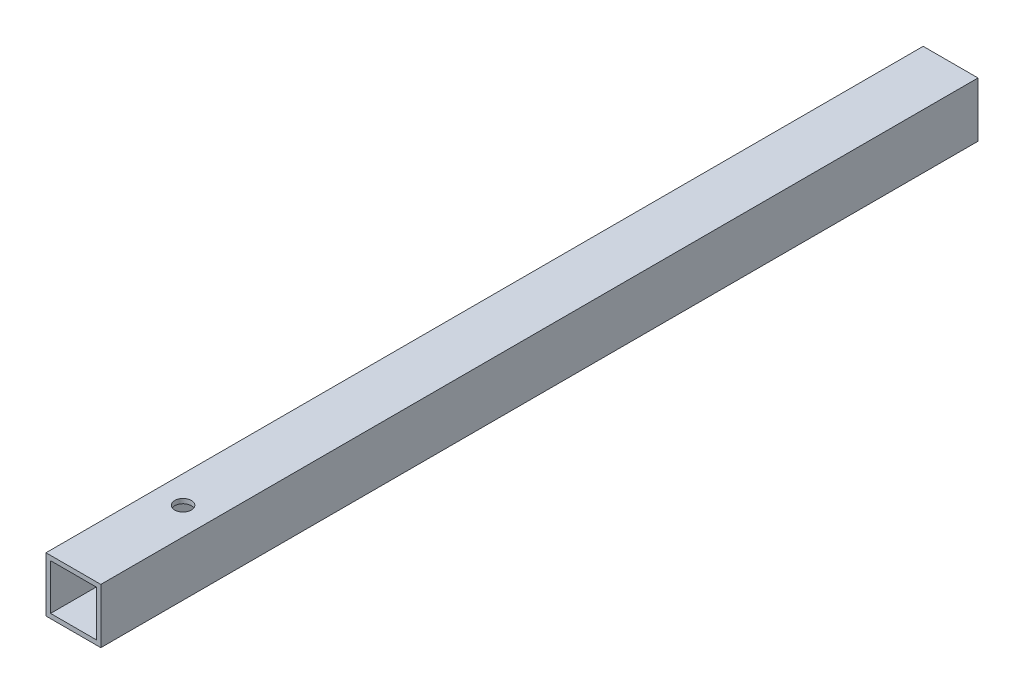
SolidWorks part; units mm, degrees
ref_plane "Front Plane" through (0, 0, 0) normal (0, 0, 1) x (1, 0, 0)
ref_plane "Top Plane" through (0, 0, 0) normal (0, 1, 0) x (1, 0, 0)
ref_plane "Right Plane" through (0, 0, 0) normal (1, 0, 0) x (0, 0, -1)
sketch "Sketch1" plane through (0, 0, 0) normal (0, 0, 1) x (0, -1, 0)
  line L1 (-9.525, 9.525) -> (9.525, 9.525)
  line L2 (-9.525, 9.525) -> (-9.525, -9.525)
  line L3 (-9.525, -9.525) -> (9.525, -9.525)
  line L4 (9.525, 9.525) -> (9.525, -9.525)
  line L5 (-9.525, 9.525) -> (9.525, -9.525) construction
  line L6 (-9.525, -9.525) -> (9.525, 9.525) construction
  line L7 (-7.9375, 7.9375) -> (7.9375, 7.9375)
  line L8 (-7.9375, 7.9375) -> (-7.9375, -7.9375)
  line L9 (-7.9375, -7.9375) -> (7.9375, -7.9375)
  line L10 (7.9375, 7.9375) -> (7.9375, -7.9375)
  line L11 (-7.9375, 7.9375) -> (7.9375, -7.9375) construction
  line L12 (-7.9375, -7.9375) -> (7.9375, 7.9375) construction
  point P0 (0, 0)
  point P5 (0, 0)
  dimension "D1" = 15.875
  dimension "D2" = 19.05
extrude "Boss-Extrude1" add sketch "Sketch1" along normal mid plane 304.8
sketch "Sketch2" plane through (0, 9.525, 0) normal (0, 1, 0) x (1, 0, 0)
  line L0 (0, -152.4) -> (0, -114.3) construction
  line L1 (9.525, -152.4) -> (-9.525, -152.4) construction
  circle A0 centre (0, -114.3) radius 2.8956
  dimension "D1" = 5.7912
  dimension "D2" = 38.1
extrude "Baseplate Mount Hole" cut sketch "Sketch2" against normal through all
sketch "Sketch3" plane through (-9.525, 0, 0) normal (-1, 0, 0) x (0, 0, 1)
  line L0 (-25.4, 0) -> (0, 0) construction
  line L1 (152.4, 9.525) -> (152.4, -9.525) construction
  circle A0 centre (-25.4, 0) radius 2.4257
  dimension "D2" = 4.8514
  dimension "D1" = 177.8
extrude "PS Bracket Mount Hole" cut sketch "Sketch3" against normal up to next
equation "\"Height\"= 32in"
equation "\"Width\"= 23in"
equation "\"Depth\"= 20in"
equation "\"Plexi\"= .121in"
equation "\"MagnetThickness\"=3mm"
equation "\"MagnetDiameter\"=12mm"
equation "\"DoorPlexi\" = \"Plexi\""
equation "\"BasePlateThickness\" = 0.5in"
equation "\"BasePlateWidth\" = \"Width\"+\"EBWidth\"-2*\"Plexi\""
equation "\"BasePlateDepth\" = \"Depth\"-\"Plexi\"-\"DoorPlexi\""
equation "\"Boxsize\" = .75in"
equation "\"Boxinner\" = .625in"
equation "\"CornerCube\" = 0.75in"
equation "\"FingerLength\" = 1.125in"
equation "\"FingerWidth\" = .625in"
equation "\"Cutwidth\"= .016in"
equation "\"Earsize\"= 1in + \"Cutwidth\" /2"
equation "\"Slotsize\" = 1in - \"CutWidth\" / 2"
equation "\"InnerWidth\" = \"Width\" - 2* \"Plexi\""
equation "\"InnerHeight\" = \"Height\" -2 * \"Plexi\""
equation "\"InnerDepth\" = \"Depth\" - 2*\"Plexi\""
equation "\"RearNumHoles\" = 7"
equation "\"RearHolesBorder\" = 2.2"
equation "\"RearHoleSpacing\" = (\"Width\" - 2*\"RearHolesBorder\") / (\"RearNumHoles\"-1)"
equation "\"RearBarLength\" = (\"InnerWidth\"-2*\"CornerCube\")"
equation "\"RearTopNumHoles\" = 6"
equation "\"RearTopHolesBorder\" = 2.5"
equation "\"RearTopHolesSpacing\" = (\"Width\" - 2*\"RearTopHolesBorder\") / (\"RearTopNumHoles\"-1)"
equation "\"SideTopNumHoles\" = 5"
equation "\"SideTopHoleOffset\"=\"CornerCube\"+\"FingerLength\"+\"Plexi\"+.5"
equation "\"SideHorizNumHoles\" = 6"
equation "\"SideHorizHoleBorder\" = 2.25"
equation "\"SideVertBarLength\"=\"Height\"-\"BasePlateThickness\"-2*\"CornerCube\"-\"Plexi\""
equation "\"SideVertNumHoles\" = 6"
equation "\"SideVertHolesBorder\" = \"CornerCube\"+\"FingerLength\"+.9"
equation "\"SideVertHoleSpacing\" = (\"InnerHeight\" - 2*\"SideVertHolesBorder\") / (\"SideVertNumHoles\"-1)"
equation "\"RearSideVertNumHoles\" = 7"
equation "\"RearSideVertHolesBorder\" = 2.5"
equation "\"RearSideVertHoleSpacing\" = (\"InnerHeight\" - 2*\"RearSideVertHolesBorder\") / (\"RearSideVertNumHoles\"-1)"
equation "\"RivetDia\" = .228in"
equation "\"SlotDepth\" = \"Plexi\" + 0.75in + .005in"
equation "\"SideSlotWidth\"   = \"Plexi\"+.005in"
equation "\"SidePanelVertSpacing\" = (\"Height\"-2*(1.75-\"Plexi\")) / 5"
equation "\"BottomPanelSideHoleSpacing\" = (\"InnerDepth\"-2*(1.75-\"Plexi\")) / 4"
equation "\"FrontDoorGap\" = .1in"
equation "\"TopDepth\" = \"Depth\"-\"DoorPlexi\"-\"FrontDoorGap\""
equation "\"TopBarDepth\" = \"Depth\"-\"DoorPlexi\"-\"Plexi\"-2*\"MagnetThickness\"-2*\"CornerCube\""
equation "\"CoolerDepth\" = 12in"
equation "\"D1@Boss-Extrude1\"=\"CoolerDepth\""
equation "\"EBWidth\" = 9in"
equation "\"ComponentMountDia\"=0.1770"
equation "\"ShelfThickness\" = .220in"
equation "\"BoxsizeHalf\" = \"Boxsize\"/2"
equation "\"SideTopHoleSpacing\" = (\"TopBarDepth\"-2*\"SideTopHoleOffset\") / (\"SideTopNumHoles\"-1)"
equation "\"SideHorizHoleSpacing\" = (\"TopBarDepth\"-2*\"SideHorizHoleBorder\") / (\"SideHorizNumHoles\"-1)"
equation "\"BinderPostDia\" = .228in"
equation "\"ShelfGap\" = 0.5in"
equation "\"ShelfDepth\" = \"TopBarDepth\"+\"CornerCube\"-\"CoolerDepth\""
equation "\"ShelfBarDepth\"=\"ShelfDepth\"-2*\"CornerCube\""
equation "\"ShelfWidth\" = \"EBWidth\"-\"ShelfGap\""
equation "\"ShelfBarWidth\" = \"EBWidth\"-\"Boxsize\""
equation "\"ShelfBarWidthShort\" = \"ShelfBarWidth\"-\"Boxsize\"-\"ShelfGap\""
equation "\"ShelfHeight1\" = 13in"
equation "\"ShelfHeight2\" = 24in"
equation "\"IntakeWidth\"=4in"
equation "\"IntakeHeight\"=2in"
equation "\"ExhaustWidth\"=4in"
equation "\"ExhaustHeight\"=2in"
equation "\"VentSpacing\"=7in"
equation "\"VentVertLocation\"=12.75in"
equation "\"AngleBracketLength\"=20mm"
equation "\"AngleBracketWidth\"=10mm"
equation "\"AngleBracketThickness\"=1.5mm"
equation "\"AngleBracketHolePos\"=15mm"
equation "\"AngleBracketHoleDia\"=\"RivetDia\""
equation "\"ShelfBarAngleHole\"=\"ShelfGap\"+\"Boxsize\"+\"AngleBracketHolePos\""
equation "\"PSBracketThickness\" = .0641in"
equation "\"EBForwardMountOffset\" = 4.0in"
equation "\"EBForwardMount\" = 2*\"Boxsize\"+\"CoolerDepth\"+\"EBForwardMountOffset\""
equation "\"D1@Sketch2\"=\"BinderPostDia\""
equation "\"EBRearwardMountOffset\" = 1.5in"
equation "\"EBRearwardMount\"= \"Boxsize\"+\"EBRearwardMountOffset\""
equation "\"D2@Sketch2\"=\"EBRearwardMountOffset\""
equation "\"Rivet3_16Dia\" = .191in"
equation "\"D2@Sketch3\"=\"Rivet3_16Dia\""
